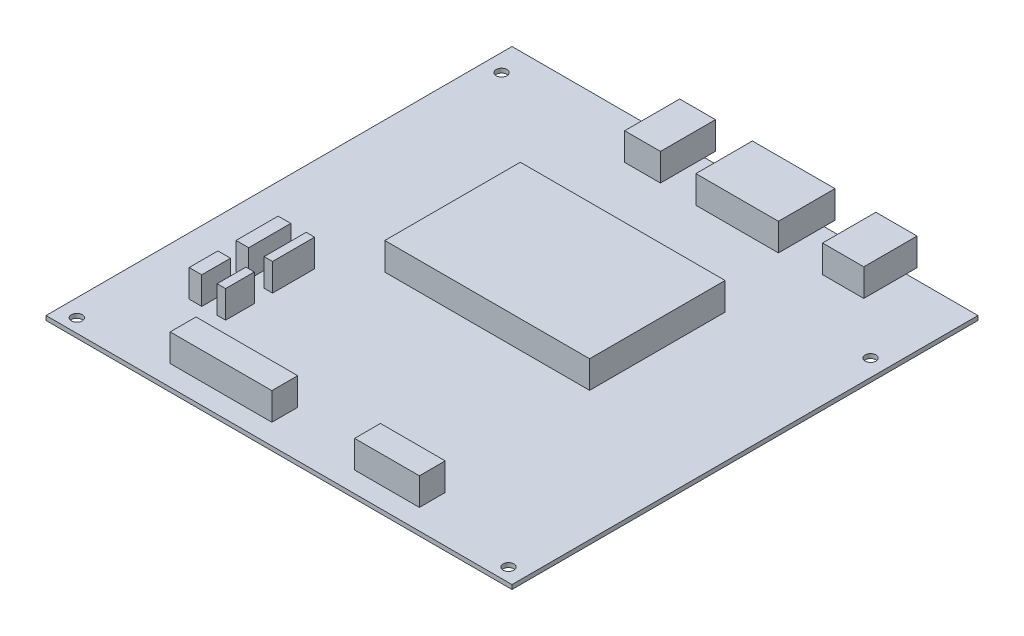
SolidWorks part; units mm, degrees
material "Skleněné vlákno-A"
ref_plane "Přední rovina" through (0, 0, 0) normal (0, 0, 1) x (1, 0, 0)
ref_plane "Horní rovina" through (0, 0, 0) normal (0, 1, 0) x (1, 0, 0)
ref_plane "Pravá rovina" through (0, 0, 0) normal (1, 0, 0) x (0, 0, -1)
sketch "Skica1" plane through (0, 0, 0) normal (0, 1, 0) x (1, 0, 0)
  line L0 (-85, 85) -> (85, -85) construction
  line L1 (-85, 85) -> (85, 85)
  line L2 (-85, 85) -> (-85, -85)
  line L3 (-85, -85) -> (85, -85)
  line L4 (85, 85) -> (85, -85)
  dimension "D1" = 170
  dimension "D2" = 170
extrude "Přidat vysunutím1" add sketch "Skica1" along normal blind 1.57
sketch "Skica2" plane through (0, 1.57, 0) normal (0, 1, 0) x (1, 0, 0)
  line L0 (85, 85) -> (-85, 85) construction
  line L1 (-85, 85) -> (-85, -85) construction
  circle A0 centre (-78.65, 74.84) radius 1.98
  circle A1 centre (-78.65, -80.1) radius 1.98
  circle A2 centre (78.83, -80.1) radius 1.98
  circle A3 centre (78.83, 51.98) radius 1.98
  dimension "D2" = 154.94
  dimension "D3" = 157.48
  dimension "D4" = 6.35
  dimension "D5" = 22.86
  dimension "D6" = 3.96
  dimension "D1" = 10.16
extrude "Odebrat vysunutím1" cut sketch "Skica2" against normal through all
sketch "Skica5" plane through (0, 1.57, 0) normal (0, 1, 0) x (1, 0, 0)
  line L1 (-36.9126, -9.4939) -> (37.8024, -9.4939)
  line L2 (-36.9126, -9.4939) -> (-36.9126, 39.943)
  line L3 (-36.9126, 39.943) -> (37.8024, 39.943)
  line L4 (37.8024, -9.4939) -> (37.8024, 39.943)
  line L5 (-27.8259, 68.9257) -> (-14.767, 68.9257)
  line L6 (-27.8259, 68.9257) -> (-27.8259, 89)
  line L7 (-27.8259, 89) -> (-14.767, 89)
  line L8 (-14.767, 68.9257) -> (-14.767, 89)
  line L9 (-1.2971, 68.3699) -> (28.8262, 68.3699)
  line L10 (-1.2971, 68.3699) -> (-1.2971, 89)
  line L11 (-1.2971, 89) -> (28.8262, 89)
  line L12 (28.8262, 68.3699) -> (28.8262, 89)
  line L13 (43.738, 69.5561) -> (58.7781, 69.5561)
  line L14 (43.738, 69.5561) -> (43.738, 89)
  line L15 (43.738, 89) -> (58.7781, 89)
  line L16 (58.7781, 69.5561) -> (58.7781, 89)
  line L17 (85, 85) -> (-85, 85) construction
  line L20 (-47.1787, -68.093) -> (-10.078, -68.093)
  line L21 (-47.1787, -68.093) -> (-47.1787, -77.5253)
  line L22 (-47.1787, -77.5253) -> (-10.078, -77.5253)
  line L23 (-10.078, -68.093) -> (-10.078, -77.5253)
  line L24 (20.1055, -68.093) -> (43.738, -68.093)
  line L25 (20.1055, -68.093) -> (20.1055, -77.5253)
  line L26 (20.1055, -77.5253) -> (43.738, -77.5253)
  line L27 (43.738, -68.093) -> (43.738, -77.5253)
  line L28 (-64.0618, -21.2524) -> (-59.4577, -21.2524)
  line L29 (-64.0618, -21.2524) -> (-64.0618, -36.5995)
  line L30 (-64.0618, -36.5995) -> (-59.4577, -36.5995)
  line L31 (-59.4577, -21.2524) -> (-59.4577, -36.5995)
  line L32 (-53.8305, -21.2524) -> (-50.7611, -21.2524)
  line L33 (-53.8305, -21.2524) -> (-53.8305, -36.5995)
  line L34 (-53.8305, -36.5995) -> (-50.7611, -36.5995)
  line L35 (-50.7611, -21.2524) -> (-50.7611, -36.5995)
  line L36 (-64.0618, -43.2393) -> (-59.4577, -43.2393)
  line L37 (-64.0618, -43.2393) -> (-64.0618, -53.7244)
  line L38 (-64.0618, -53.7244) -> (-59.4577, -53.7244)
  line L39 (-59.4577, -43.2393) -> (-59.4577, -53.7244)
  line L40 (-53.8305, -43.2393) -> (-50.7611, -43.2393)
  line L41 (-53.8305, -43.2393) -> (-53.8305, -53.7244)
  line L42 (-53.8305, -53.7244) -> (-50.7611, -53.7244)
  line L43 (-50.7611, -43.2393) -> (-50.7611, -53.7244)
  dimension "D1" = 4
extrude "Přidat vysunutím3" add sketch "Skica5" along normal blind 10
sketch "Skica3" plane through (-85, 0, 0) normal (-1, 0, 0) x (0, 0, 1)
  line L1 (-87.11, 42.21) -> (-88.11, 42.21)
  line L2 (-87.11, 42.21) -> (-87.11, -2.24)
  line L3 (-87.11, -2.24) -> (-88.11, -2.24)
  line L4 (-88.11, 42.21) -> (-88.11, -2.24)
  line L5 (-74.84, 0) -> (-74.84, 1.57) construction
  line L6 (85, 0) -> (-85, 0) construction
  dimension "D1" = 2.24
  dimension "D2" = 12.27
  dimension "D3" = 1
  dimension "D4" = 44.45
extrude "Přidat vysunutím2" [suppressed] add sketch "Skica3" against normal blind 182 separate body
sketch "Skica4" [suppressed] plane through (0, 0, -88.11) normal (0, 0, -1) x (-1, 0, 0)
  line L0 (-97, 42.21) -> (85, 42.21) construction
  line L1 (-88.07, 42.21) -> (70.68, 42.21)
  line L2 (-88.07, 42.21) -> (-88.07, -2.24)
  line L3 (-88.07, -2.24) -> (70.68, -2.24)
  line L4 (70.68, 42.21) -> (70.68, -2.24)
  line L5 (-97, -2.24) -> (85, -2.24) construction
  line L6 (78.65, 0) -> (78.65, 1.57) construction
  dimension "D1" = 158.75
  dimension "D2" = 7.97
extrude "Odebrat vysunutím2" [suppressed] cut sketch "Skica4" against normal through all flip side to cut
